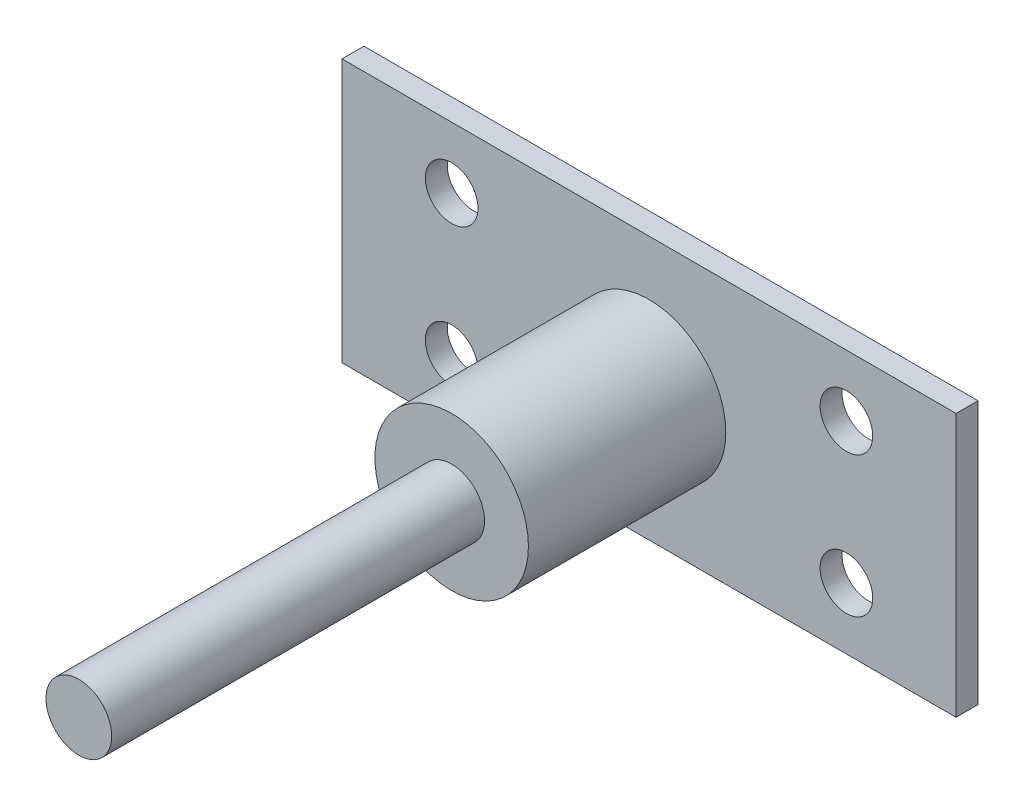
SolidWorks part; units mm, degrees
ref_plane "Front Plane" through (0, 0, 0) normal (0, 0, 1) x (1, 0, 0)
ref_plane "Top Plane" through (0, 0, 0) normal (0, 1, 0) x (1, 0, 0)
ref_plane "Right Plane" through (0, 0, 0) normal (1, 0, 0) x (0, 0, -1)
sketch "Sketch1" plane through (0, 0, 0) normal (0, 0, 1) x (1, 0, 0)
  line L0 (0, 30) -> (0, -30) construction
  line L1 (-70, 30) -> (70, 30)
  line L2 (-70, 30) -> (-70, -30)
  line L3 (-70, -30) -> (70, -30)
  line L4 (70, 30) -> (70, -30)
  line L5 (-70, 30) -> (70, -30) construction
  line L6 (-70, -30) -> (70, 30) construction
  circle A0 centre (-45, 16) radius 6
  circle A1 centre (-45, -16) radius 6
  circle A3 centre (45, -16) radius 6
  circle A4 centre (45, 16) radius 6
  point P0 (0, 0)
  dimension "D3" = 12
  dimension "D4" = 12
  dimension "D5" = 12
  dimension "D6" = 12
  dimension "D7" = 45
  dimension "D8" = 45
  dimension "D9" = 45
  dimension "D10" = 45
  dimension "D11" = 14
  dimension "D12" = 14
  dimension "D13" = 14
  dimension "D14" = 14
  dimension "D1" = 140
  dimension "D2" = 60
extrude "Boss-Extrude1" add sketch "Sketch1" along normal blind 5
sketch "Sketch2" plane through (0, 0, 5) normal (0, 0, 1) x (1, 0, 0)
  circle A0 centre (0, 0) radius 17.5
  dimension "D1" = 35
extrude "Boss-Extrude2" add sketch "Sketch2" along normal blind 45
sketch "Sketch3" plane through (0, 0, 50) normal (0, 0, 1) x (1, 0, 0)
  circle A0 centre (0, 0) radius 7.5
  dimension "D1" = 15
extrude "Boss-Extrude3" add sketch "Sketch3" along normal blind 85
